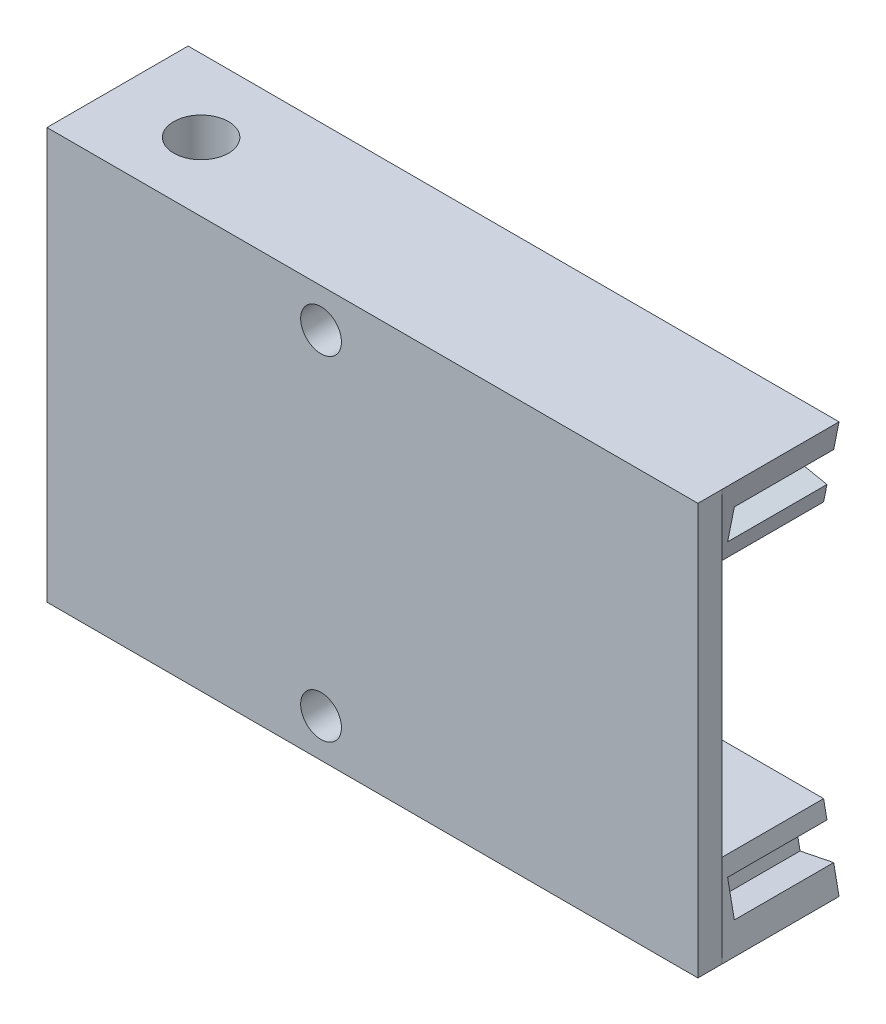
SolidWorks part; units mm, degrees
ref_plane "Front Plane" through (0, 0, 0) normal (0, 0, 1) x (1, 0, 0)
ref_plane "Top Plane" through (0, 0, 0) normal (0, 1, 0) x (1, 0, 0)
ref_plane "Right Plane" through (0, 0, 0) normal (1, 0, 0) x (0, 0, -1)
sketch "Sketch1" plane through (0, 0, 0) normal (0, 1, 0) x (1, 0, 0)
  line L1 (0, 0) -> (15, 0)
  line L2 (0, 0) -> (0, 4.12)
  line L3 (0, 4.12) -> (15, 4.12)
  line L4 (15, 0) -> (15, 4.12)
extrude "Boss-Extrude1" add sketch "Sketch1" along normal blind 12
sketch "Sketch3" plane through (0, 0, 0) normal (-1, 0, 0) x (0, 0, 1)
  line L0 (-4.12, 12) -> (-4.12, 0) construction
  line L1 (-4.12, 2.25) -> (-0.7, 2.25)
  line L2 (-4.12, 2.25) -> (-4.12, 9.75)
  line L3 (-4.12, 9.75) -> (-0.7, 9.75)
  line L4 (-0.7, 2.25) -> (-0.7, 9.75)
extrude "Cut-Extrude1" cut sketch "Sketch3" against normal blind 25
ref_plane "Plane1" through (0, 6, 0) normal (0, -1, 0) x (-1, 0, 0)
sketch "Sketch5" plane through (0, 0, -4.12) normal (0, 0, -1) x (-1, 0, 0)
  line L0 (-15, 12) -> (-14.55, 9.75)
  line L1 (-15, 12) -> (-15, 9.75)
  line L2 (-15, 9.75) -> (-14.55, 9.75)
  line L3 (-15, 9.75) -> (0, 9.75) construction
extrude "Cut-Extrude3" cut sketch "Sketch5" against normal up to vertex (3.42 mm away)
mirror "Mirror2" about plane through (0, 6, 0) normal (0, -1, 0) of "Cut-Extrude3"
sketch "Sketch7" plane through (12.1154, -2.4231, 0) normal (0.9806, -0.1961, 0) x (0, 0, -1)
  line L0 (4.12, 12.4142) -> (4.12, 14.7087) construction
  line L1 (4.12, 12.9142) -> (1.22, 12.9142)
  line L2 (4.12, 12.9142) -> (4.12, 13.9142)
  line L3 (4.12, 13.9142) -> (1.22, 13.9142)
  line L4 (1.22, 12.9142) -> (1.22, 13.9142)
  line L5 (0.7, 12.4142) -> (4.12, 12.4142) construction
  dimension "D1" = 0.5
extrude "Cut-Extrude4" cut sketch "Sketch7" against normal blind 1
hole_wizard "#0-80 Tapped Hole1" positions "Sketch11" profile "Sketch10" tap size "#0-80" standard "ANSI Inch"
sketch "Sketch11" plane through (0, 0, -4.12) normal (0, 0, -1) x (-1, 0, 0)
  line L0 (0, 12) -> (0, 9.75) construction
  point P0 (-4, 10.875)
  dimension "D1" = 4
sketch "Sketch10" plane through (4, 10.875, -4.12) normal (1, 0, 0) x (0, 1, 0)
  line L0 (0, 0) -> (0, 5.3079)
  line L1 (0, 5.3079) -> (0.5956, 4.95)
  line L2 (0.5956, 4.95) -> (0.5956, 0)
  line L5 (0.5956, 0) -> (0, 0)
  line L10 (0, 5.3079) -> (-0.5956, 4.95) construction
  line L11 (0, -6.35) -> (0, 107.95) construction
  dimension "Tap Drill Dia." = 1.1913
  dimension "Tap Drill Depth" = 4.95
  dimension "Drill Angle" = 118
sketch "Sketch12" plane through (0, 0, 0) normal (-1, 0, 0) x (0, 0, 1)
  line L0 (0, 0) -> (0, 12)
  line L1 (0, 12) -> (-4.12, 12)
  line L2 (-4.12, 12) -> (-4.12, 9.75)
  line L3 (-4.12, 9.75) -> (-0.7, 9.75)
  line L4 (-0.7, 9.75) -> (-0.7, 2.25)
  line L5 (-0.7, 2.25) -> (-4.12, 2.25)
  line L6 (-4.12, 2.25) -> (-4.12, 0)
  line L7 (-4.12, 0) -> (0, 0)
extrude "Boss-Extrude2" add sketch "Sketch12" along normal blind 4
hole_wizard "M2x0.4 Tapped Hole1" positions "Sketch16" profile "Sketch15" tap size "M2x0.4" standard "ANSI Metric"
sketch "Sketch16" plane through (0, 12, 0) normal (0, 1, 0) x (1, 0, 0)
  line L0 (-4, 0) -> (-4, 4.12) construction
  line L1 (-4, 0) -> (15, 0) construction
  point P0 (-1.5, 2)
  dimension "D1" = 2.5
  dimension "D2" = 2
sketch "Sketch15" plane through (-1.5, 12, -2) normal (1, 0, 0) x (0, 0, 1)
  line L0 (0, 0) -> (0, 5.6807)
  line L1 (0, 5.6807) -> (0.8, 5.2)
  line L2 (0.8, 5.2) -> (0.8, 0)
  line L5 (0.8, 0) -> (0, 0)
  line L10 (0, 5.6807) -> (-0.8, 5.2) construction
  line L11 (0, -6.35) -> (0, 107.95) construction
  dimension "Tap Drill Dia." = 1.6
  dimension "Tap Drill Depth" = 5.2
  dimension "Drill Angle" = 118
mirror "Mirror3" about plane through (0, 6, 0) normal (0, -1, 0) of "M2x0.4 Tapped Hole1", "#0-80 Tapped Hole1", "Cut-Extrude4"
